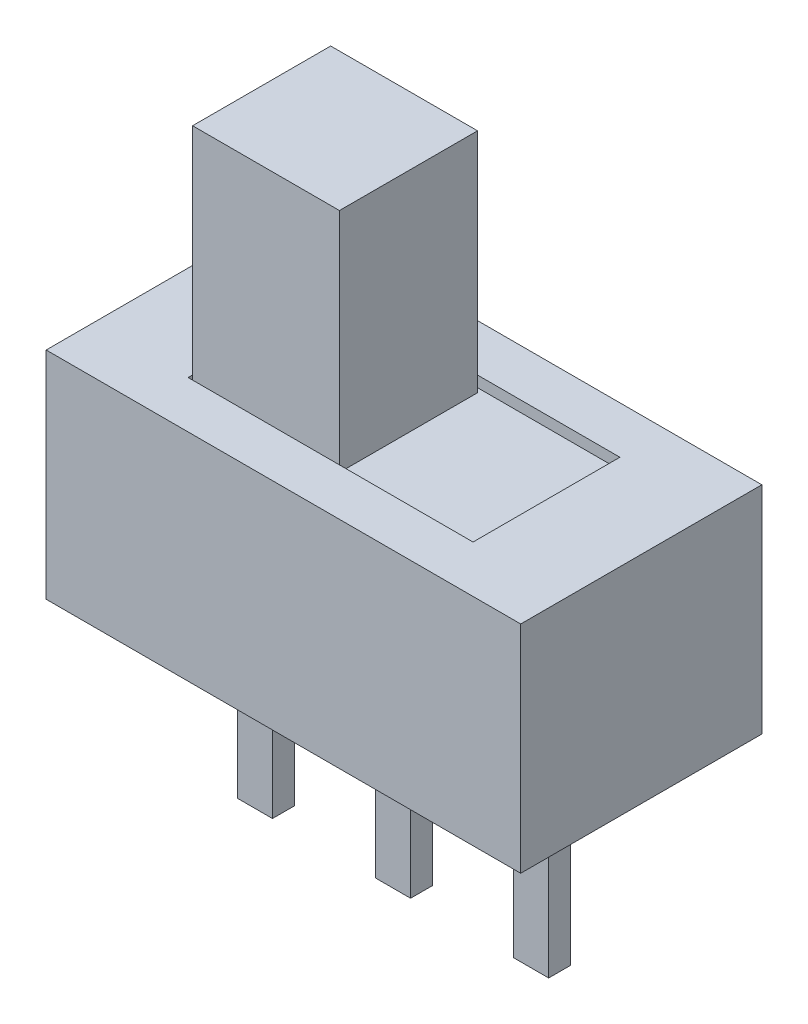
SolidWorks part; units mm, degrees
ref_plane "Front Plane" through (0, 0, 0) normal (0, 0, 1) x (1, 0, 0)
ref_plane "Top Plane" through (0, 0, 0) normal (0, 1, 0) x (1, 0, 0)
ref_plane "Right Plane" through (0, 0, 0) normal (1, 0, 0) x (0, 0, -1)
sketch "Sketch1" plane through (0, 0, 0) normal (0, 1, 0) x (1, 0, 0)
  line L1 (-5.4991, 2.794) -> (5.4991, 2.794)
  line L2 (-5.4991, 2.794) -> (-5.4991, -2.794)
  line L3 (-5.4991, -2.794) -> (5.4991, -2.794)
  line L4 (5.4991, 2.794) -> (5.4991, -2.794)
  line L5 (-5.4991, 2.794) -> (5.4991, -2.794) construction
  line L6 (-5.4991, -2.794) -> (5.4991, 2.794) construction
  point P0 (0, 0)
  dimension "D1" = 5.588
  dimension "D2" = 10.9982
extrude "Boss-Extrude1" add sketch "Sketch1" along normal blind 5.0038
sketch "Sketch2" plane through (0, 5.0038, 0) normal (0, 1, 0) x (1, 0, 0)
  line L1 (-3.302, 1.7018) -> (3.302, 1.7018)
  line L2 (-3.302, 1.7018) -> (-3.302, -1.7018)
  line L3 (-3.302, -1.7018) -> (3.302, -1.7018)
  line L4 (3.302, 1.7018) -> (3.302, -1.7018)
  line L5 (-3.302, 1.7018) -> (3.302, -1.7018) construction
  line L6 (-3.302, -1.7018) -> (3.302, 1.7018) construction
  point P0 (0, 0)
  dimension "D1" = 6.604
  dimension "D2" = 3.4036
extrude "Cut-Extrude1" cut sketch "Sketch2" against normal blind 0.254
ref_plane "Plane1" through (0, 0, 0) normal (0, 0, 1) x (1, 0, 0)
sketch "Sketch3" plane through (0, 4.7498, 0) normal (0, 1, 0) x (1, 0, 0)
  line L0 (-2.7521, 0) -> (2.7521, 0) construction
  line L1 (-3.2995, 1.6002) -> (0.1041, 1.6002)
  line L2 (-3.2995, 1.6002) -> (-3.2995, -1.6002)
  line L3 (-3.2995, -1.6002) -> (0.1041, -1.6002)
  line L4 (0.1041, 1.6002) -> (0.1041, -1.6002)
  line L5 (-3.2995, 1.6002) -> (0.1041, -1.6002) construction
  line L6 (-3.2995, -1.6002) -> (0.1041, 1.6002) construction
  line L7 (-3.302, 1.7018) -> (-3.302, -1.7018) construction
  point P0 (-1.5977, 0)
  dimension "D1" = 3.4036
  dimension "D2" = 3.2004
  dimension "D3" = 0.0025
extrude "Boss-Extrude2" add sketch "Sketch3" along normal blind 5.2578
sketch "Sketch4" plane through (0, 0, 0) normal (0, -1, 0) x (1, 0, 0)
  line L1 (-0.4064, 0.254) -> (0.4064, 0.254)
  line L2 (-0.4064, 0.254) -> (-0.4064, -0.254)
  line L3 (-0.4064, -0.254) -> (0.4064, -0.254)
  line L4 (0.4064, 0.254) -> (0.4064, -0.254)
  line L5 (-0.4064, 0.254) -> (0.4064, -0.254) construction
  line L6 (-0.4064, -0.254) -> (0.4064, 0.254) construction
  point P0 (0, 0)
  dimension "D1" = 0.8128
  dimension "D2" = 0.508
extrude "Boss-Extrude3" add sketch "Sketch4" along normal blind 4.318
pattern_linear "LPattern1" count 2 spacing 3.2004 along (1, 0, 0) count 2 spacing 3.2004 along (-1, 0, 0) of "Boss-Extrude3"
